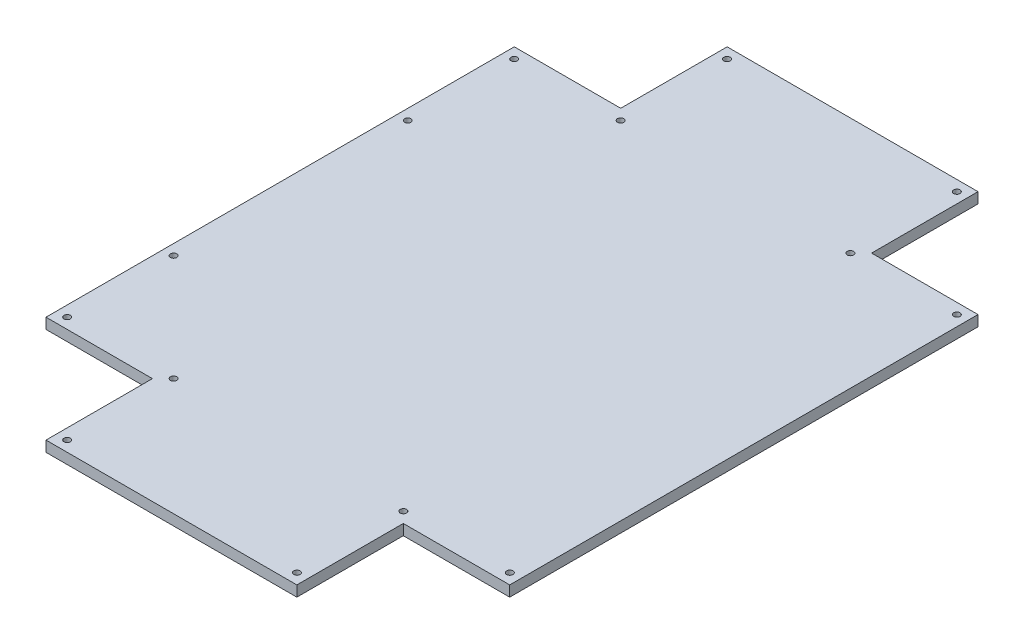
SolidWorks part; units mm, degrees
ref_plane "Plan de face" through (0, 0, 0) normal (0, 0, 1) x (1, 0, 0)
ref_plane "Plan de dessus" through (0, 0, 0) normal (0, 1, 0) x (1, 0, 0)
ref_plane "Plan de droite" through (0, 0, 0) normal (1, 0, 0) x (0, 0, -1)
sketch "Esquisse1" plane through (0, 0, 0) normal (0, 1, 0) x (1, 0, 0)
  line L0 (-58.9276, 110) -> (-58.9276, 160)
  line L1 (108.9276, -110) -> (58.9276, -110)
  line L2 (108.9276, -110) -> (108.9276, 110)
  line L3 (108.9276, 110) -> (58.9276, 110)
  line L4 (-108.9276, -110) -> (-108.9276, 0)
  line L5 (108.9276, -110) -> (-108.9276, 110) construction
  line L6 (108.9276, 110) -> (-108.9276, -110) construction
  line L7 (-58.9276, 160) -> (58.9276, 160)
  line L8 (58.9276, 160) -> (58.9276, 110)
  line L9 (0, 160) -> (0, -89.8749) construction
  line L10 (-108.9276, 0) -> (108.9276, 0) construction
  line L11 (-103.9763, -105) -> (-103.9763, -50) construction
  line L12 (-53.9763, -105) -> (-53.9763, -160) construction
  line L13 (-58.9276, 110) -> (-108.9276, 110)
  line L14 (58.9276, -160) -> (58.9276, -110)
  line L15 (-58.9276, -160) -> (58.9276, -160)
  line L16 (-58.9276, -110) -> (-58.9276, -160)
  line L17 (-58.9276, -110) -> (-108.9276, -110)
  line L28 (-108.9276, 0) -> (-108.9276, 110)
  line L33 (-103.9763, -105) -> (103.9763, -105) construction
  line L34 (103.9763, -105) -> (103.9763, 0) construction
  circle A0 centre (-103.9763, -105) radius 1.5
  circle A1 centre (-103.9763, -55) radius 1.5
  circle A2 centre (-53.9763, -105) radius 1.5
  circle A5 centre (-3.9763, -105) radius 1.5 [skipped]
  circle A6 centre (46.0237, -105) radius 1.5 [skipped]
  circle A7 centre (-53.9763, -155) radius 1.5
  circle A8 centre (-53.9763, 155) radius 1.5
  circle A9 centre (-53.9763, 105) radius 1.5
  circle A10 centre (-103.9763, 105) radius 1.5
  circle A11 centre (-103.9763, 55) radius 1.5
  circle A12 centre (53.9763, -155) radius 1.5
  circle A13 centre (53.9763, -105) radius 1.5
  circle A14 centre (103.9763, -105) radius 1.5
  circle A15 centre (103.9763, 105) radius 1.5
  circle A16 centre (53.9763, 105) radius 1.5
  circle A17 centre (53.9763, 155) radius 1.5
  point P0 (0, 0)
  point P24 (0, 0)
  point P33 (0, 0)
  dimension "D4" = 3
  dimension "D6" = 50
  dimension "D14" = 5
  dimension "D16" = 5
  dimension "D1" = 220
  dimension "D2" = 50
  dimension "D3" = 50
  dimension "D5" = 5
  dimension "D13" = 2
  dimension "D15" = 4
  dimension "D17" = 2
extrude "Boss.-Extru.1" add sketch "Esquisse1" along normal blind 5
